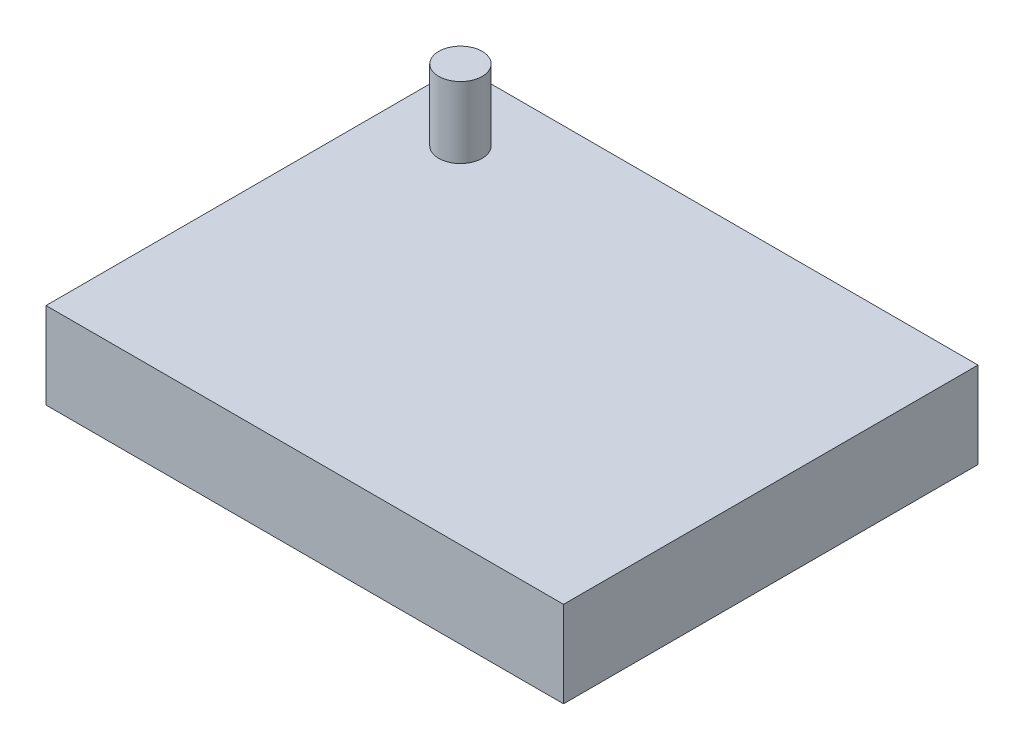
SolidWorks part; units mm, degrees
material "Cast Alloy Steel"
ref_plane "Front Plane" through (0, 0, 0) normal (0, 0, 1) x (1, 0, 0)
ref_plane "Top Plane" through (0, 0, 0) normal (0, 1, 0) x (1, 0, 0)
ref_plane "Right Plane" through (0, 0, 0) normal (1, 0, 0) x (0, 0, -1)
sketch "Sketch1" plane through (0, 0, 0) normal (0, 1, 0) x (1, 0, 0)
  line L0 (0, 76.3302) -> (0, -76.3302) construction
  line L1 (-95.3185, -76.3302) -> (95.3185, -76.3302)
  line L2 (-95.3185, -76.3302) -> (-95.3185, 76.3302)
  line L3 (-95.3185, 76.3302) -> (95.3185, 76.3302)
  line L4 (95.3185, -76.3302) -> (95.3185, 76.3302)
  point P4 (95.3185, 76.3302)
extrude "Boss-Extrude1" add sketch "Sketch1" along normal blind 31.75
sketch "Sketch7" plane through (0, 31.75, 0) normal (0, 1, 0) x (1, 0, 0)
  line L0 (-95.3185, 76.3302) -> (-95.3185, -76.3302) construction
  line L1 (95.3185, 76.3302) -> (-95.3185, 76.3302) construction
  circle A0 centre (-69.9185, 50.9302) radius 8.001
  dimension "D1" = 16.002
  dimension "D2" = 25.4
  dimension "D3" = 25.4
extrude "Boss-Extrude2" add sketch "Sketch7" along normal blind 26.162
